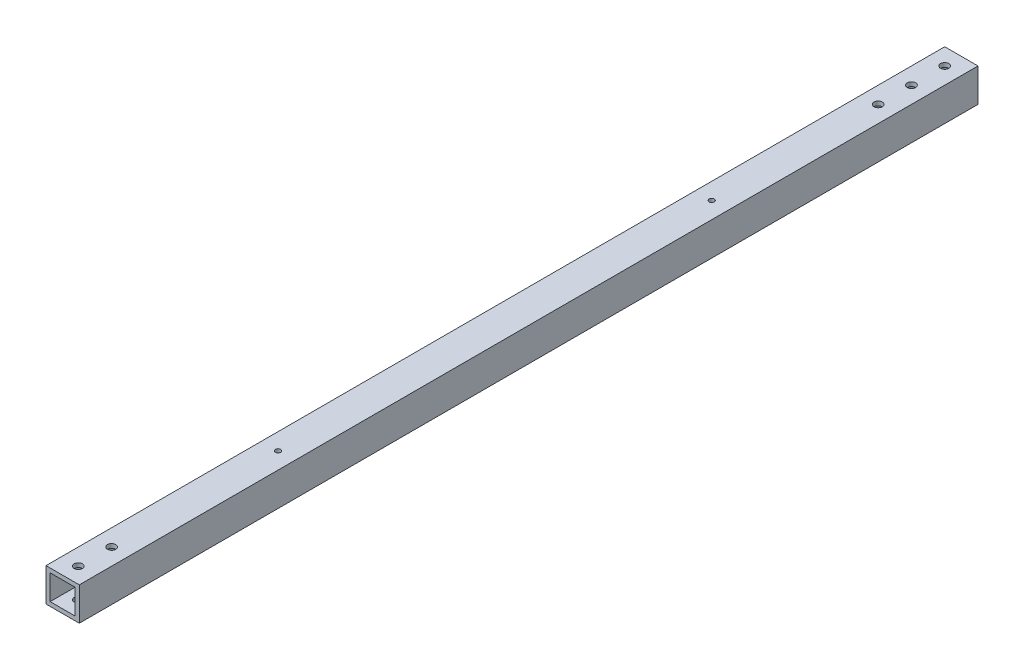
SolidWorks part; units mm, degrees
ref_plane "Front Plane" through (0, 0, 0) normal (0, 0, 1) x (1, 0, 0)
ref_plane "Top Plane" through (0, 0, 0) normal (0, 1, 0) x (1, 0, 0)
ref_plane "Right Plane" through (0, 0, 0) normal (1, 0, 0) x (0, 0, -1)
sketch "Sketch1" plane through (0, 0, 0) normal (0, 0, 1) x (1, 0, 0)
  line L0 (-9.525, 9.525) -> (9.525, 9.525)
  line L2 (-12.7, 12.7) -> (12.7, 12.7)
  line L3 (-12.7, 12.7) -> (-12.7, -12.7)
  line L4 (-12.7, -12.7) -> (12.7, -12.7)
  line L5 (12.7, 12.7) -> (12.7, -12.7)
  line L10 (9.525, 9.525) -> (9.525, -9.525)
  line L11 (-9.525, -9.525) -> (9.525, -9.525)
  line L12 (-9.525, 9.525) -> (-9.525, -9.525)
  point P12 (0, 12.7)
  point P14 (12.7, 0)
  dimension "Wall Thickness" = 3.175
  dimension "Outside Width" = 25.4
  dimension "Outside Height" = 25.4
  dimension "Inside Height" = 19.05
  dimension "Inside Width" = 19.05
sketch "Sketch2" plane through (0, 0, 0) normal (1, 0, 0) x (0, 0, -1)
  line L0 (342.9, 0) -> (-342.9, 0)
  point P4 (0, 0)
  point P7 (-342.9, 0)
  point P10 (342.9, 0)
  dimension "Length" = 685.8
sketch "Sketch3" plane through (0, 0, 0) normal (0, 0, 1) x (1, 0, 0)
  line L21 (12.7, 12.7) -> (-12.7, 12.7)
  line L22 (12.7, -12.7) -> (12.7, 12.7)
  line L23 (-12.7, -12.7) -> (12.7, -12.7)
  line L24 (-12.7, 12.7) -> (-12.7, -12.7)
  line L25 (12.7, 12.7) -> (-12.7, 12.7)
  line L26 (12.7, -12.7) -> (12.7, 12.7)
  line L27 (-12.7, -12.7) -> (12.7, -12.7)
  line L28 (-12.7, 12.7) -> (-12.7, -12.7)
  line L29 (9.525, 9.525) -> (-9.525, 9.525)
  line L30 (9.525, -9.525) -> (9.525, 9.525)
  line L31 (-9.525, -9.525) -> (9.525, -9.525)
  line L32 (-9.525, 9.525) -> (-9.525, -9.525)
  line L33 (9.525, 9.525) -> (-9.525, 9.525)
  line L34 (9.525, -9.525) -> (9.525, 9.525)
  line L35 (-9.525, -9.525) -> (9.525, -9.525)
  line L36 (-9.525, 9.525) -> (-9.525, -9.525)
  dimension "D1" = 0
  dimension "D2" = 0
extrude "Boss-Extrude1" add sketch "Sketch3" along normal up to vertex (342.9 mm away) and the other way up to vertex (342.9 mm away) up to point (0, 0, 342.9) other way up to point (0, 0, -342.9)
sketch "Drawing Reference" plane through (0, 0, 0) normal (1, 0, 0) x (0, 0, -1)
  line L0 (-342.9, 0) -> (342.9, 0) construction
  line L1 (0, -12.7) -> (0, 12.7) construction
  line L2 (-342.9, -12.7) -> (342.9, -12.7) construction
  line L5 (-342.9, 12.7) -> (342.9, 12.7) construction
  point P7 (-324.612, 0)
  point P8 (324.612, 0)
  dimension "D1" = 18.288
sketch "Sketch4" plane through (0, 12.7, 0) normal (0, 1, 0) x (1, 0, 0)
  line L0 (0, -342.9) -> (0, -178.5118)
  line L1 (12.7, -342.9) -> (-12.7, -342.9) construction
  line L2 (0, 342.9) -> (0, 152.4)
  line L3 (12.7, 342.9) -> (-12.7, 342.9) construction
hole_wizard "5/32 (0.15625) Diameter Hole1" positions "Sketch5" profile "Sketch6" hole size "5/32" standard "ANSI Inch" end condition through all
sketch "Sketch5" plane through (0, 12.7, 0) normal (0, 1, 0) x (1, 0, 0)
  point P0 (0, 152.4)
  point P3 (0, -178.5118)
sketch "Sketch6" plane through (0, 12.7, -152.4) normal (1, 0, 0) x (0, 0, 1)
  line L0 (0, 0) -> (0, 25.4)
  line L1 (0, 25.4) -> (1.9844, 25.4)
  line L2 (1.9844, 25.4) -> (1.9844, 0)
  line L5 (1.9844, 0) -> (0, 0)
  line L11 (0, -6.35) -> (0, 107.95) construction
  dimension "Thru Hole Dia." = 3.9688
  dimension "Thru Hole Depth" = 25.4
sketch "Sketch7" plane through (0, 12.7, 0) normal (0, 1, 0) x (1, 0, 0)
  line L0 (0, 342.9) -> (0, 330.2)
  line L1 (0, 330.2) -> (0, 304.8)
  line L2 (0, 342.9) -> (0, 152.4) construction
  line L3 (0, 304.8) -> (0, 279.4)
hole_wizard "1/4 (0.25) Diameter Hole1" positions "Sketch8" profile "Sketch9" hole size "1/4" standard "ANSI Inch" end condition through all
sketch "Sketch8" plane through (0, 12.7, 0) normal (0, 1, 0) x (1, 0, 0)
  point P0 (0, 330.2)
  point P3 (0, 304.8)
  point P6 (0, 279.4)
sketch "Sketch9" plane through (0, 12.7, -330.2) normal (1, 0, 0) x (0, 0, 1)
  line L0 (0, 0) -> (0, 25.4)
  line L1 (0, 25.4) -> (3.175, 25.4)
  line L2 (3.175, 25.4) -> (3.175, 0)
  line L5 (3.175, 0) -> (0, 0)
  line L11 (0, -6.35) -> (0, 107.95) construction
  dimension "Thru Hole Dia." = 6.35
  dimension "Thru Hole Depth" = 25.4
sketch "Sketch10" plane through (0, 12.7, 0) normal (0, 1, 0) x (1, 0, 0)
  line L0 (0, -342.9) -> (0, -330.9118)
  line L1 (0, -330.9118) -> (0, -305.5118)
  line L2 (0, -342.9) -> (0, -178.5118) construction
hole_wizard "1/4 (0.25) Diameter Hole2" positions "Sketch11" profile "Sketch12" hole size "1/4" standard "ANSI Inch" end condition through all
sketch "Sketch11" plane through (0, 12.7, 0) normal (0, 1, 0) x (1, 0, 0)
  point P0 (0, -330.9118)
  point P3 (0, -305.5118)
sketch "Sketch12" plane through (0, 12.7, 330.9118) normal (1, 0, 0) x (0, 0, 1)
  line L0 (0, 0) -> (0, 25.4)
  line L1 (0, 25.4) -> (3.175, 25.4)
  line L2 (3.175, 25.4) -> (3.175, 0)
  line L5 (3.175, 0) -> (0, 0)
  line L11 (0, -6.35) -> (0, 107.95) construction
  dimension "Thru Hole Dia." = 6.35
  dimension "Thru Hole Depth" = 25.4
equation "\"D1@Drawing Reference\"=\"Outside Width@Sketch1\" * 0.72"
